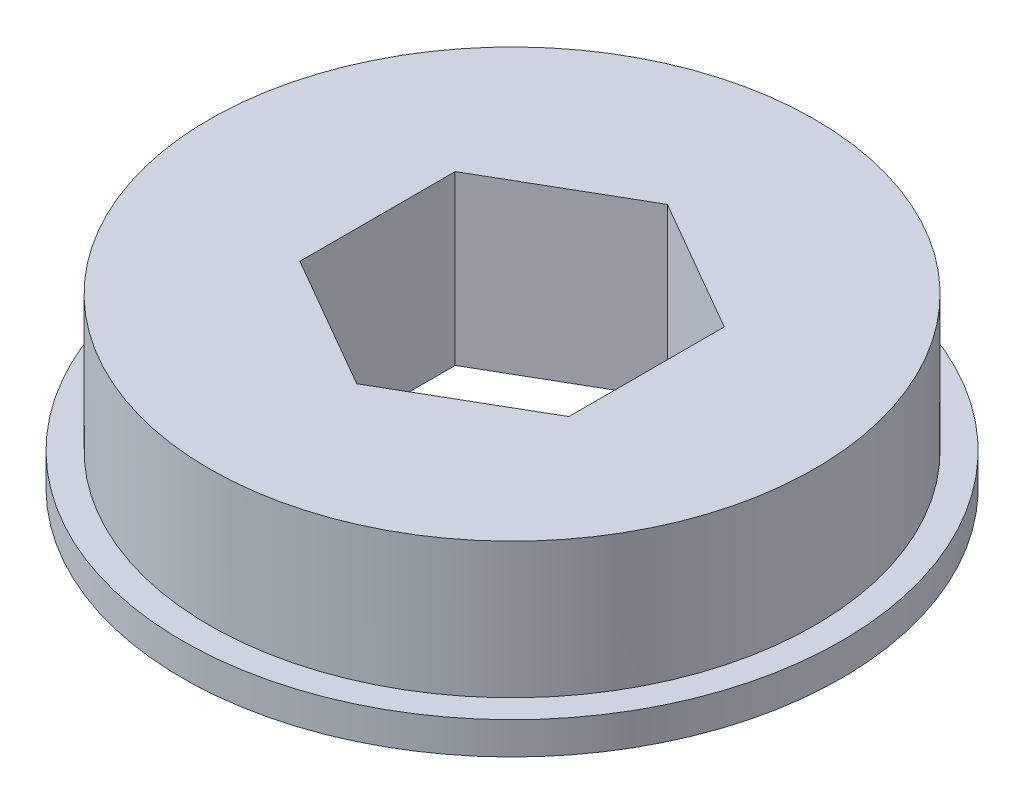
SolidWorks part; units mm, degrees
ref_plane "Front Plane" through (0, 0, 0) normal (0, 0, 1) x (1, 0, 0)
ref_plane "Top Plane" through (0, 0, 0) normal (0, 1, 0) x (1, 0, 0)
ref_plane "Right Plane" through (0, 0, 0) normal (1, 0, 0) x (0, 0, -1)
sketch "Sketch1" plane through (0, 0, 0) normal (0, 1, 0) x (1, 0, 0)
  line L1 (6.35, -3.6662) -> (6.35, 3.6662)
  line L2 (6.35, 3.6662) -> (0, 7.3323)
  line L3 (0, 7.3323) -> (-6.35, 3.6662)
  line L4 (-6.35, 3.6662) -> (-6.35, -3.6662)
  line L5 (-6.35, -3.6662) -> (0, -7.3323)
  line L6 (0, -7.3323) -> (6.35, -3.6662)
  circle A0 centre (0, 0) radius 14.2875
  circle A1 centre (0, 0) radius 6.35 construction
  point P3 (0, -14.2875)
  dimension "D1" = 28.575
  dimension "D2" = 12.7
extrude "Boss-Extrude1" add sketch "Sketch1" along normal blind 7.9248
sketch "Sketch2" plane through (0, 0, 0) normal (0, -1, 0) x (1, 0, 0)
  circle A0 centre (0, 0) radius 14.2875
  circle A1 centre (0, 0) radius 15.5575
  dimension "D1" = 28.575
  dimension "D2" = 31.115
extrude "Boss-Extrude2" add sketch "Sketch2" against normal blind 1.524
